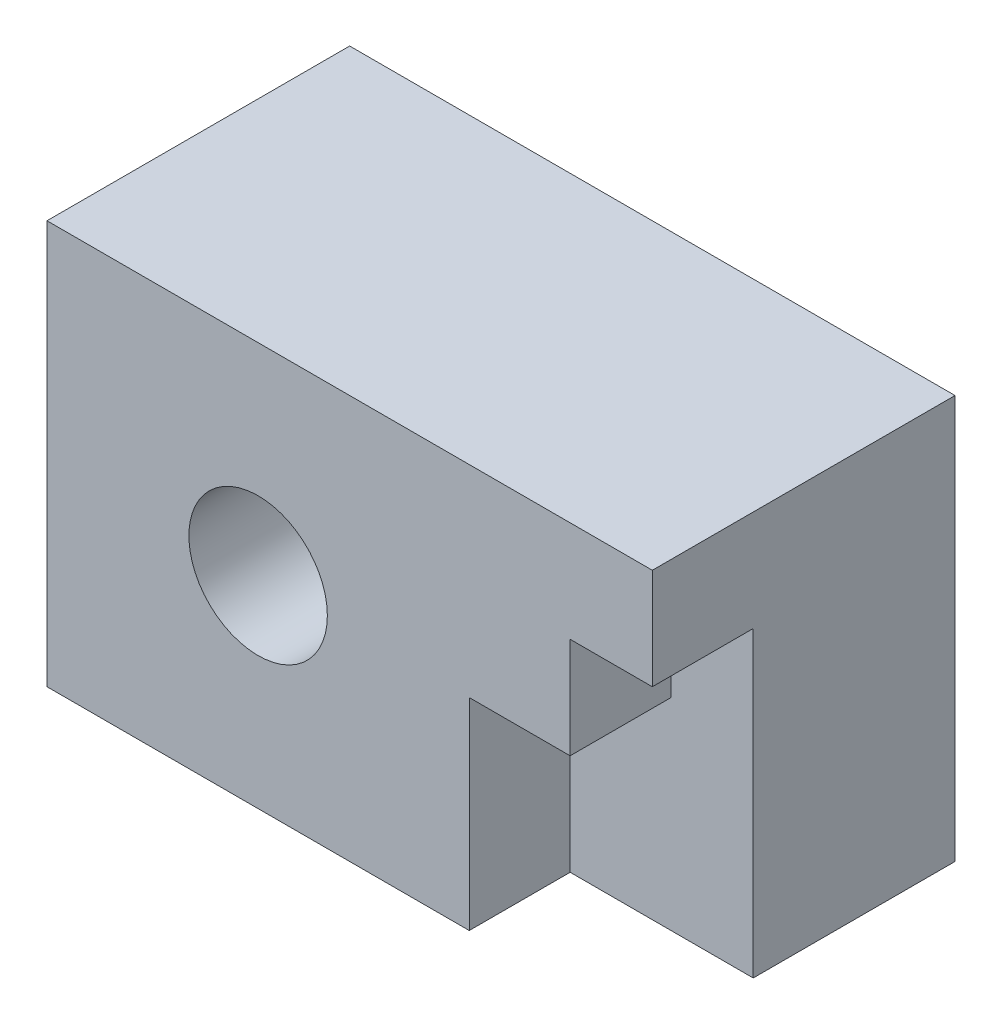
SolidWorks part; units mm, degrees
ref_plane "Front Plane" through (0, 0, 0) normal (0, 0, 1) x (1, 0, 0)
ref_plane "Top Plane" through (0, 0, 0) normal (0, 1, 0) x (1, 0, 0)
ref_plane "Right Plane" through (0, 0, 0) normal (1, 0, 0) x (0, 0, -1)
sketch "Sketch1" plane through (0, 0, 0) normal (0, 0, 1) x (1, 0, 0)
  line L1 (0, 0) -> (60, 0)
  line L2 (0, 0) -> (0, 40)
  line L3 (0, 40) -> (60, 40)
  line L4 (60, 0) -> (60, 40)
  dimension "D1" = 60
  dimension "D2" = 40
extrude "Boss-Extrude1" add sketch "Sketch1" along normal blind 30
sketch "Sketch2" plane through (0, 0, 30) normal (0, 0, 1) x (1, 0, 0)
  line L0 (41.8533, 0) -> (41.8533, 20)
  line L1 (0, 0) -> (60, 0) construction
  line L2 (41.8533, 20) -> (51.8533, 20)
  line L3 (51.8533, 20) -> (51.8533, 30)
  line L4 (51.8533, 30) -> (60, 30)
  line L5 (60, 0) -> (60, 40) construction
  line L6 (60, 30) -> (60, 0)
  line L7 (60, 0) -> (41.8533, 0)
  dimension "D1" = 20
  dimension "D2" = 10
  dimension "D3" = 10
extrude "Cut-Extrude1" cut sketch "Sketch2" against normal blind 10
sketch "Sketch3" plane through (0, 0, 30) normal (0, 0, 1) x (1, 0, 0)
  line L0 (41.8533, 20) -> (41.8533, 40) construction
  line L1 (60, 40) -> (0, 40) construction
  line L2 (41.8533, 40) -> (0, 0) construction
  line L3 (0, 40) -> (41.8533, 0) construction
  circle A0 centre (20.9266, 20) radius 6.8636
extrude "Cut-Extrude2" cut sketch "Sketch3" against normal blind 31
